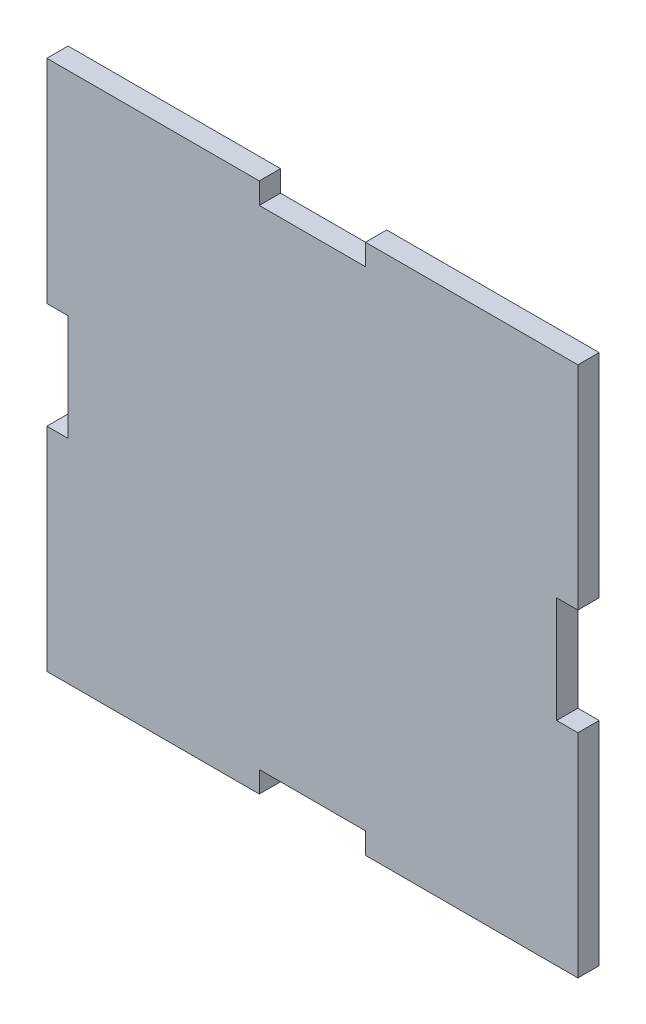
SolidWorks part; units mm, degrees
ref_plane "前视基准面" through (0, 0, 0) normal (0, 0, 1) x (1, 0, 0)
ref_plane "上视基准面" through (0, 0, 0) normal (0, 1, 0) x (1, 0, 0)
ref_plane "右视基准面" through (0, 0, 0) normal (1, 0, 0) x (0, 0, -1)
sketch "草图1" plane through (0, 0, 0) normal (0, 0, 1) x (1, 0, 0)
  line L1 (0, 0) -> (100, 0)
  line L2 (0, 0) -> (0, 100)
  line L3 (0, 100) -> (100, 100)
  line L4 (100, 0) -> (100, 100)
  line L5 (40, 100) -> (60, 100)
  line L6 (40, 100) -> (40, 96)
  line L7 (40, 96) -> (60, 96)
  line L8 (60, 100) -> (60, 96)
  line L9 (0, 60) -> (4, 60)
  line L10 (0, 60) -> (0, 40)
  line L11 (0, 40) -> (4, 40)
  line L12 (4, 60) -> (4, 40)
  line L13 (40, 0) -> (60, 0)
  line L14 (40, 0) -> (40, 4)
  line L15 (40, 4) -> (60, 4)
  line L16 (60, 0) -> (60, 4)
  line L17 (100, 60) -> (96, 60)
  line L18 (100, 60) -> (100, 40)
  line L19 (100, 40) -> (96, 40)
  line L20 (96, 60) -> (96, 40)
  point P5 (0, 40)
  point P6 (0, 60)
  point P7 (40, 100)
  point P8 (60, 100)
  point P9 (100, 60)
  point P10 (100, 40)
  point P11 (60, 0)
  point P12 (40, 0)
extrude "凸台-拉伸1" add sketch "草图1" along normal blind 4 contours L20 L17 L4 L3 L8 L7 L6 L2 L9 L12 L11 L1 L14 L15 L16 L19
